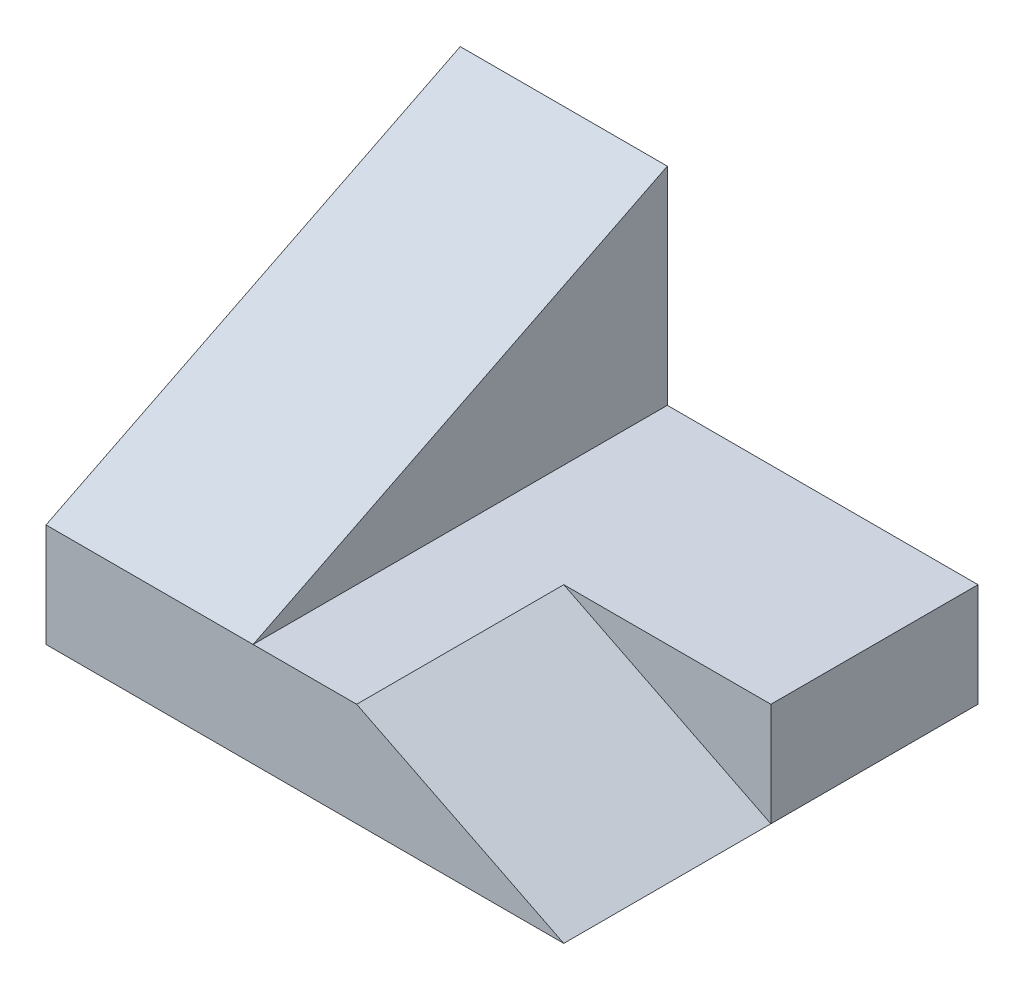
SolidWorks part; units mm, degrees
ref_plane "Front Plane" through (0, 0, 0) normal (0, 0, 1) x (1, 0, 0)
ref_plane "Top Plane" through (0, 0, 0) normal (0, 1, 0) x (1, 0, 0)
ref_plane "Right Plane" through (0, 0, 0) normal (1, 0, 0) x (0, 0, -1)
sketch "Sketch1" plane through (0, 0, 0) normal (0, 1, 0) x (1, 0, 0)
  line L1 (-63.5, -50.8) -> (63.5, -50.8)
  line L2 (-63.5, -50.8) -> (-63.5, 50.8)
  line L3 (-63.5, 50.8) -> (63.5, 50.8)
  line L4 (63.5, -50.8) -> (63.5, 50.8)
  line L5 (-63.5, -50.8) -> (63.5, 50.8) construction
  line L6 (-63.5, 50.8) -> (63.5, -50.8) construction
  point P0 (0, 0)
  dimension "D1" = 127
  dimension "D2" = 101.6
extrude "Boss-Extrude1" add sketch "Sketch1" along normal blind 25.4
sketch "Sketch2" plane through (0, 0, 50.8) normal (0, 0, 1) x (1, 0, 0)
  line L0 (63.5, 0) -> (12.7, 25.4)
  line L1 (-63.5, 25.4) -> (63.5, 25.4) construction
  line L2 (12.7, 25.4) -> (63.5, 25.4)
  line L3 (63.5, 25.4) -> (63.5, 0)
  dimension "D1" = 50.8
extrude "Cut-Extrude1" cut sketch "Sketch2" against normal blind 50.8
sketch "Sketch3" plane through (-63.5, 0, 0) normal (-1, 0, 0) x (0, 0, 1)
  line L0 (-50.8, 25.4) -> (-50.8, 76.2)
  line L1 (-50.8, 76.2) -> (50.8, 25.4)
  line L2 (50.8, 25.4) -> (-50.8, 25.4)
  dimension "D1" = 50.8
extrude "Boss-Extrude2" add sketch "Sketch3" against normal blind 50.8 separate body
